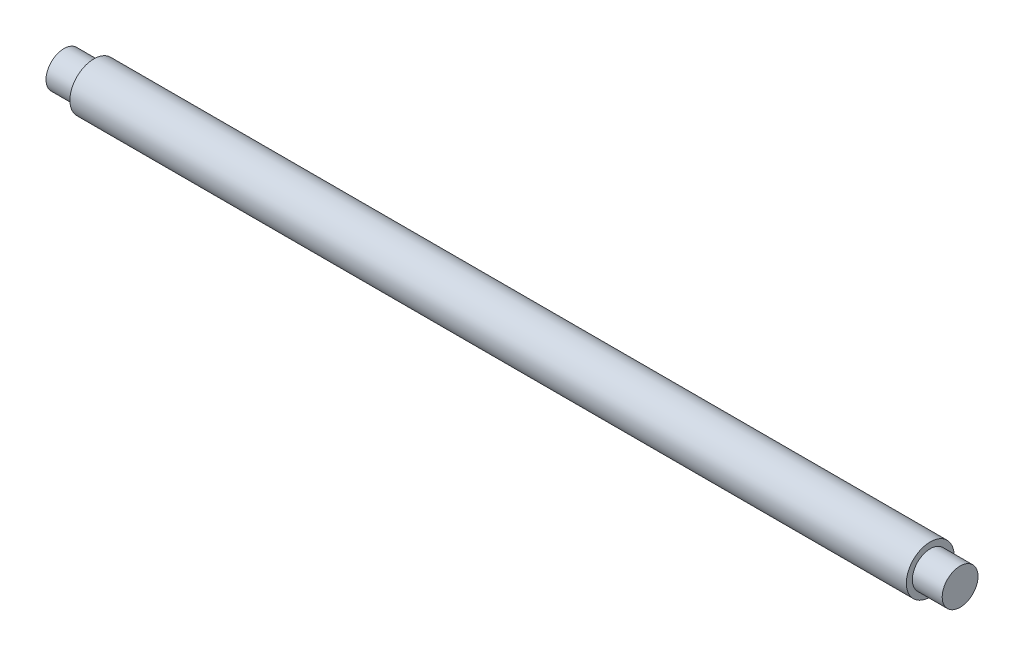
SolidWorks part; units mm, degrees
material "201 Annealed Stainless Steel (SS)"
ref_plane "Front Plane" through (0, 0, 0) normal (0, 0, 1) x (1, 0, 0)
ref_plane "Top Plane" through (0, 0, 0) normal (0, 1, 0) x (1, 0, 0)
ref_plane "Right Plane" through (0, 0, 0) normal (1, 0, 0) x (0, 0, -1)
sketch "Sketch1" plane through (0, 0, 0) normal (0, 1, 0) x (1, 0, 0)
  line L0 (-203.9841, 0) -> (-53.9841, 0) construction
  line L1 (-203.9841, 0) -> (-203.9841, 3)
  line L2 (-203.9841, 3) -> (-198.9841, 3)
  line L3 (-198.9841, 3) -> (-198.9841, 4)
  line L4 (-198.9841, 4) -> (-58.9841, 4)
  line L5 (-58.9841, 4) -> (-58.9841, 3)
  line L6 (-58.9841, 3) -> (-53.9841, 3)
  line L7 (-53.9841, 3) -> (-53.9841, 0)
  line L8 (-203.9841, 0) -> (-53.9841, 0)
  dimension "D1" = 150
  dimension "D2" = 3
  dimension "D3" = 3
  dimension "D4" = 5
  dimension "D5" = 5
  dimension "D6" = 4
revolve "Revolve1" add sketch "Sketch1" angle 360 about L0
